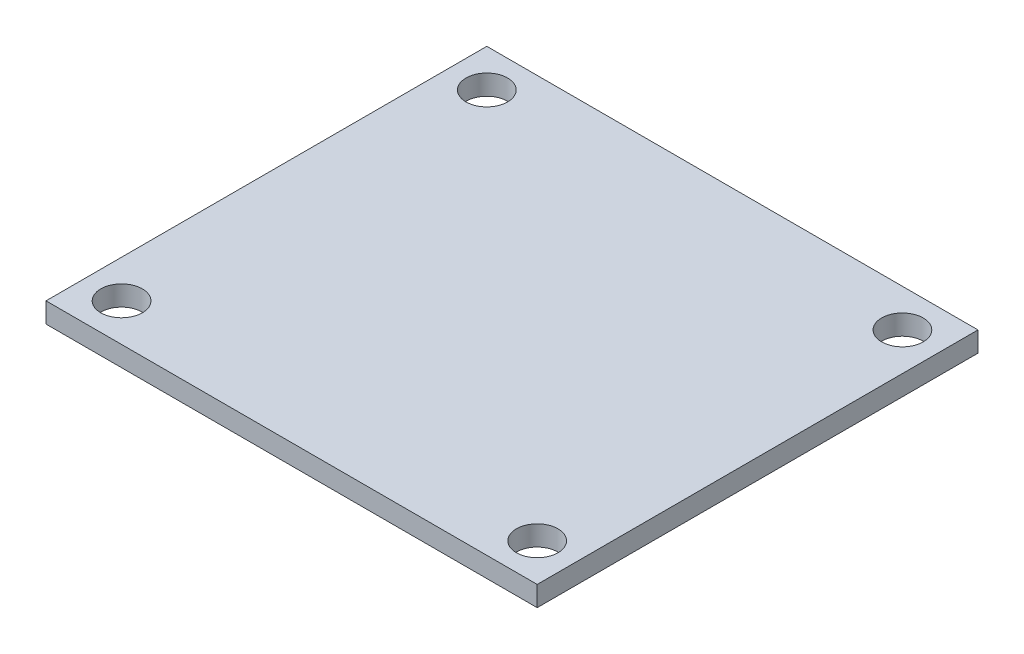
SolidWorks part; units mm, degrees
material "AISI 1015 Steel, Cold Drawn (SS)"
ref_plane "Front Plane" through (0, 0, 0) normal (0, 0, 1) x (1, 0, 0)
ref_plane "Top Plane" through (0, 0, 0) normal (0, 1, 0) x (1, 0, 0)
ref_plane "Right Plane" through (0, 0, 0) normal (1, 0, 0) x (0, 0, -1)
sketch "Sketch1" plane through (0, 0, 0) normal (0, 1, 0) x (1, 0, 0)
  line L0 (-16.5, 14.5) -> (16.5, 14.5) construction
  line L1 (19.5, -17.5) -> (-19.5, -17.5)
  line L2 (19.5, -17.5) -> (19.5, 17.5)
  line L3 (19.5, 17.5) -> (-19.5, 17.5)
  line L4 (-19.5, -17.5) -> (-19.5, 17.5)
  line L5 (0, 17.5) -> (0, -17.5) construction
  line L6 (19.5, 0) -> (-19.5, 0) construction
  line L7 (-16.5, 14.5) -> (-16.5, -14.5) construction
  circle A0 centre (16.5, -14.5) radius 1.65
  circle A1 centre (-16.5, -14.5) radius 1.65
  circle A2 centre (-16.5, 14.5) radius 1.65
  circle A3 centre (16.5, 14.5) radius 1.65
  point P0 (0, 0)
  point P15 (0, 14.5)
  point P16 (-16.5, 0)
  dimension "D3" = 33
  dimension "D5" = 3.3
  dimension "D1" = 39
  dimension "D2" = 35
  dimension "D4" = 29
extrude "Boss-Extrude1" add sketch "Sketch1" along normal blind 1.6
